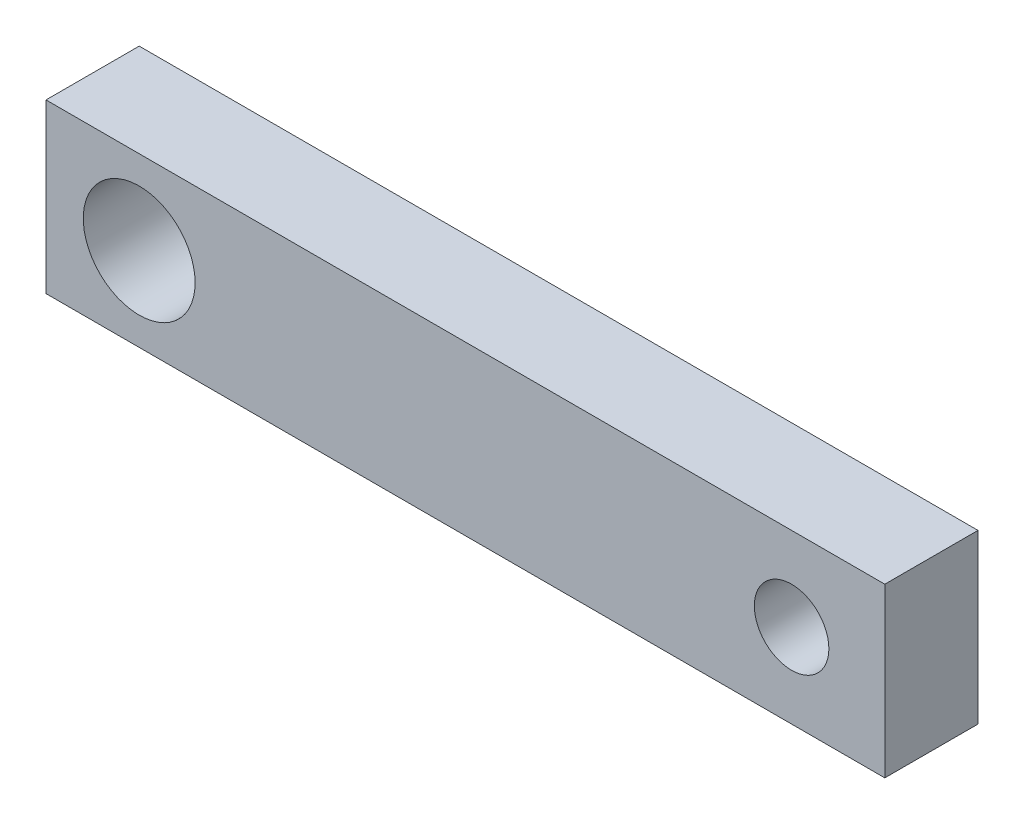
SolidWorks part; units mm, degrees
ref_plane "Front Plane" through (0, 0, 0) normal (0, 0, 1) x (1, 0, 0)
ref_plane "Top Plane" through (0, 0, 0) normal (0, 1, 0) x (1, 0, 0)
ref_plane "Right Plane" through (0, 0, 0) normal (1, 0, 0) x (0, 0, -1)
sketch "Sketch1" plane through (0, 0, 0) normal (0, 0, 1) x (1, 0, 0)
  line L1 (-20, -18) -> (160, -18)
  line L2 (-20, -18) -> (-20, 18)
  line L3 (-20, 18) -> (160, 18)
  line L4 (160, -18) -> (160, 18)
  circle A0 centre (0, 0) radius 12
  circle A1 centre (140, 0) radius 8
extrude "Boss-Extrude1" add sketch "Sketch1" along normal blind 20
